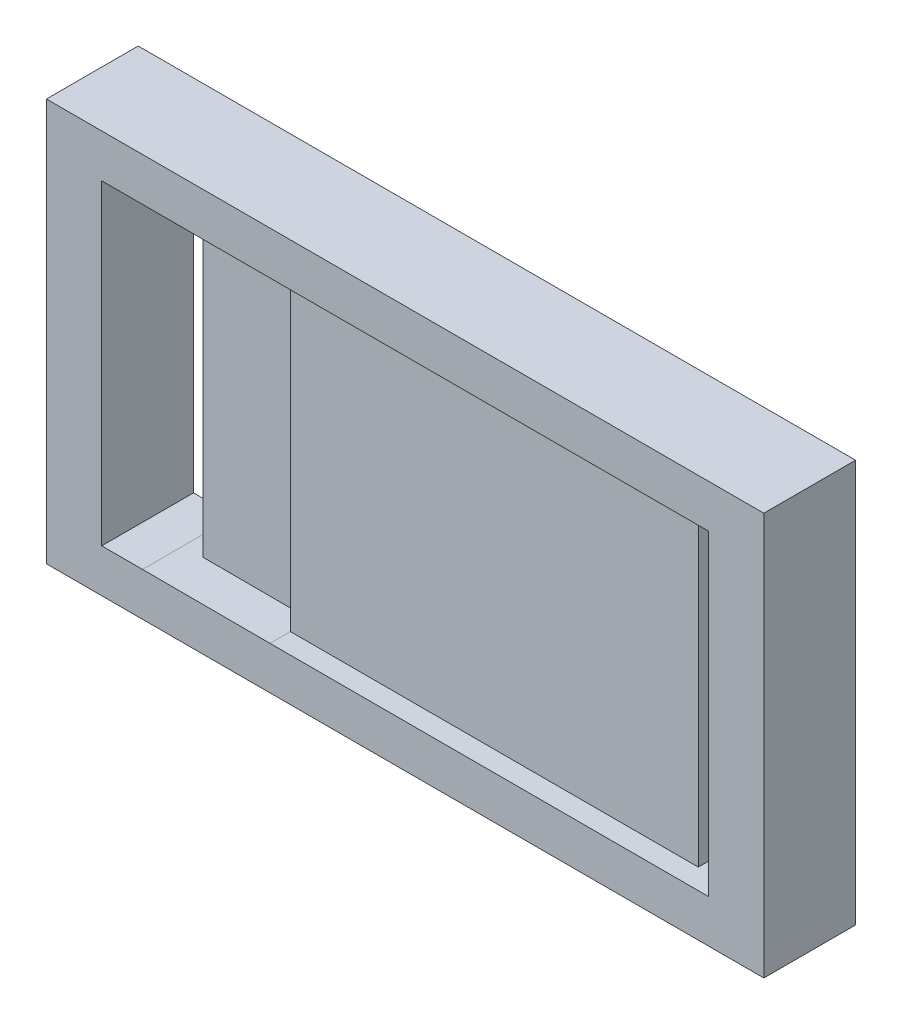
SolidWorks part; units mm, degrees
ref_plane "前视基准面" through (0, 0, 0) normal (0, 0, 1) x (1, 0, 0)
ref_plane "上视基准面" through (0, 0, 0) normal (0, 1, 0) x (1, 0, 0)
ref_plane "右视基准面" through (0, 0, 0) normal (1, 0, 0) x (0, 0, -1)
other "Configuration Table"
sketch "草图1" plane through (0, 0, 0) normal (0, 0, 1) x (1, 0, 0)
  line L1 (-59.5, -31) -> (59.5, -31)
  line L2 (-59.5, -31) -> (-59.5, 31)
  line L3 (-59.5, 31) -> (59.5, 31)
  line L4 (59.5, -31) -> (59.5, 31)
  line L5 (-59.5, -31) -> (59.5, 31) construction
  line L6 (-59.5, 31) -> (59.5, -31) construction
  line L7 (-70.3484, -39.4741) -> (70.3484, -39.4741)
  line L8 (-70.3484, -39.4741) -> (-70.3484, 39.4741)
  line L9 (-70.3484, 39.4741) -> (70.3484, 39.4741)
  line L10 (70.3484, -39.4741) -> (70.3484, 39.4741)
  line L11 (-70.3484, -39.4741) -> (70.3484, 39.4741) construction
  line L12 (-70.3484, 39.4741) -> (70.3484, -39.4741) construction
  point P0 (0, 0)
  point P6 (0, 0)
  dimension "D1" = 119
  dimension "D2" = 62
extrude "凸台-拉伸1" add sketch "草图1" along normal blind 10 and the other way blind 8
sketch "草图2" plane through (0, 0, 0) normal (0, 0, 1) x (1, 0, 0)
  line L0 (59.5, 31) -> (59.5, -31)
  line L1 (59.5, -31) -> (-51.5, -31)
  line L2 (-59.5, -31) -> (59.5, -31) construction
  line L3 (-51.5, -31) -> (-51.5, 31)
  line L4 (59.5, 31) -> (-59.5, 31) construction
  line L5 (-51.5, 31) -> (59.5, 31)
extrude "凸台-拉伸2" add sketch "草图2" along normal blind 10
sketch "草图3" plane through (0, 0, 10) normal (0, 0, 1) x (1, 0, 0)
  line L0 (-51.5, 31) -> (-26.5, 31)
  line L1 (-26.5, 31) -> (-26.5, -31.0616)
  line L2 (-26.5, -31.0616) -> (-51.5, -31)
  line L3 (-51.5, -31) -> (-51.5, 31)
  dimension "D1" = 25
extrude "切除-拉伸1" cut sketch "草图3" against normal blind 8
sketch "草图4" plane through (0, 0, 2) normal (0, 0, 1) x (1, 0, 0)
  line L0 (-51.5, 31) -> (-47.6036, 31)
  line L1 (-26.5, 31) -> (-51.5, 31) construction
  line L2 (-47.6036, 31) -> (-47.6036, -31.0096)
  line L3 (-51.5, -31) -> (-26.5, -31.0616) construction
  line L4 (-47.6036, -31.0096) -> (-51.5, -31)
  line L5 (-51.5, -31) -> (-51.5, 31)
extrude "切除-拉伸2" cut sketch "草图4" against normal through all
sketch "草图5" plane through (0, 0, 10) normal (0, 0, 1) x (1, 0, 0)
  line L0 (59.4984, -31.0616) -> (53.4984, -31.0616)
  line L1 (53.4984, -31.0616) -> (53.4984, 31)
  line L2 (53.4984, 31) -> (59.4984, 31)
  line L3 (59.4984, 31) -> (59.4984, -31.0616)
  line L4 (70.3484, -39.4741) -> (70.3484, 39.4741) construction
  dimension "D1" = 10.85
  dimension "D2" = 6
extrude "切除-拉伸3" cut sketch "草图5" against normal through all
sketch "草图6" plane through (0, 0, 10) normal (0, 0, 1) x (1, 0, 0)
  line L0 (-26.5, 31) -> (53.4984, 31)
  line L1 (53.4984, 31) -> (53.4984, -31.0616)
  line L2 (53.4984, -31.0616) -> (-26.5, -31.0616)
  line L3 (-26.5, -31.0616) -> (-26.5, 31) construction
  line L4 (-26.5, -31.0616) -> (-26.5, 31)
extrude "切除-拉伸4" cut sketch "草图6" against normal blind 4
